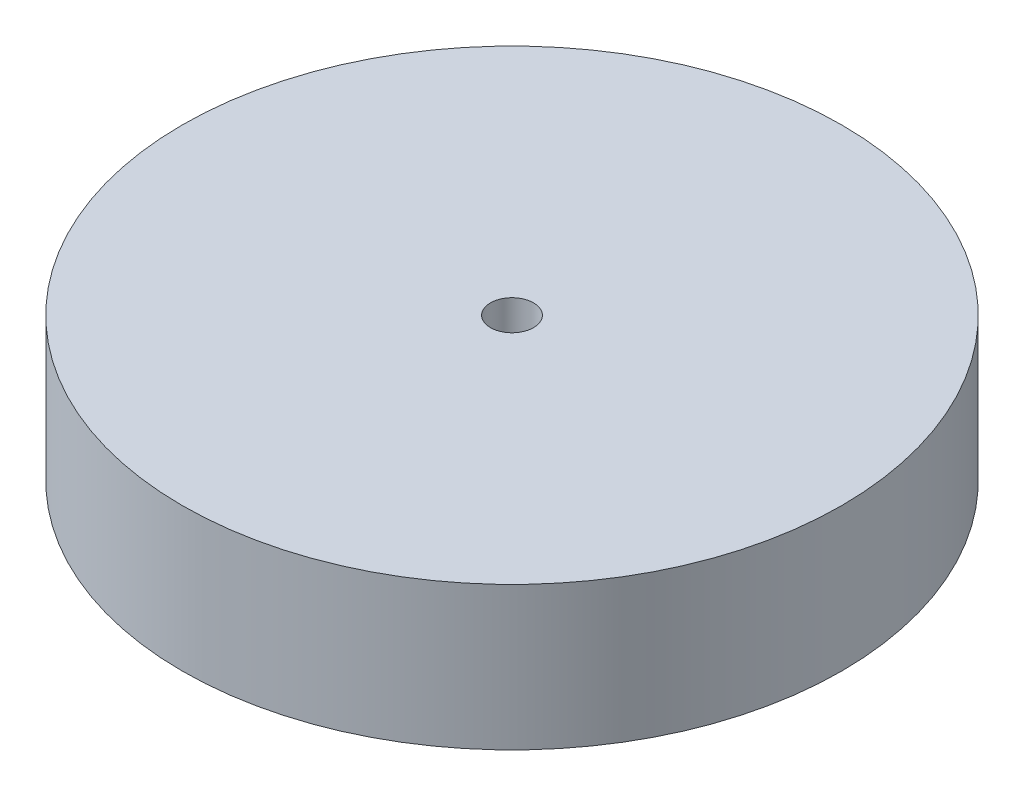
SolidWorks part; units mm, degrees
ref_plane "Front Plane" through (0, 0, 0) normal (0, 0, 1) x (1, 0, 0)
ref_plane "Top Plane" through (0, 0, 0) normal (0, 1, 0) x (1, 0, 0)
ref_plane "Right Plane" through (0, 0, 0) normal (1, 0, 0) x (0, 0, -1)
sketch "Sketch1" plane through (0, 0, 0) normal (0, 1, 0) x (1, 0, 0)
  circle A0 centre (0, 0) radius 23
extrude "Boss-Extrude1" add sketch "Sketch1" along normal blind 10
sketch "Sketch2" plane through (0, 0, 0) normal (0, -1, 0) x (1, 0, 0)
  circle A0 centre (0, 0) radius 20
extrude "Cut-Extrude1" cut sketch "Sketch2" against normal blind 7.3 contours A0
sketch "Sketch3" plane through (0, 7.3, 0) normal (0, -1, 0) x (1, 0, 0)
  circle A0 centre (0, 0) radius 6
extrude "Boss-Extrude3" add sketch "Sketch3" along normal blind 14.5
sketch "Sketch4" plane through (0, -7.2, 0) normal (0, -1, 0) x (1, 0, 0)
  circle A0 centre (0, 0) radius 1.5
extrude "Cut-Extrude2" cut sketch "Sketch4" against normal up to surface (17.2 mm away) up to face at (0, 10, 23)
